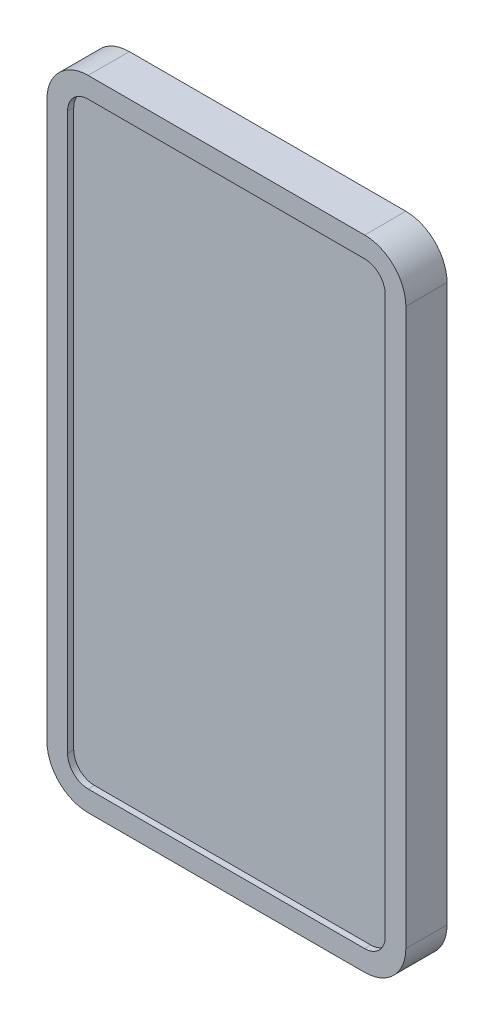
SolidWorks part; units mm, degrees
ref_plane "Plan de face" through (0, 0, 0) normal (0, 0, 1) x (1, 0, 0)
ref_plane "Plan de dessus" through (0, 0, 0) normal (0, 1, 0) x (1, 0, 0)
ref_plane "Plan de droite" through (0, 0, 0) normal (1, 0, 0) x (0, 0, -1)
sketch "Esquisse1" plane through (0, 0, 0) normal (0, 0, 1) x (1, 0, 0)
  line L1 (-67.1082, -155) -> (67.1082, -155)
  line L2 (-87.1082, -135) -> (-87.1082, 135)
  line L3 (-67.1082, 155) -> (67.1082, 155)
  line L4 (87.1082, -135) -> (87.1082, 135)
  line L5 (-87.1082, -155) -> (87.1082, 155) construction
  line L6 (-87.1082, 155) -> (87.1082, -155) construction
  arc A0 (87.1082, -153) -> (85.1082, -155) centre (85.1082, -153) cw
  arc A1 (-85.1082, -155) -> (-87.1082, -153) centre (-85.1082, -153) cw
  arc A2 (-87.1082, 153) -> (-85.1082, 155) centre (-85.1082, 153) cw
  arc A3 (87.1082, 153) -> (85.1082, 155) centre (85.1082, 153) ccw
  arc A4 (-87.1082, -135) -> (-67.1082, -155) centre (-67.1082, -135) ccw
  arc A5 (67.1082, -155) -> (87.1082, -135) centre (67.1082, -135) ccw
  arc A6 (87.1082, 135) -> (67.1082, 155) centre (67.1082, 135) ccw
  arc A7 (-67.1082, 155) -> (-87.1082, 135) centre (-67.1082, 135) ccw
  point P0 (0, 0)
  dimension "D3" = 2
  dimension "D4" = 20
  dimension "D1" = 355.6
  dimension "D2" = 310
extrude "Boss.-Extru.1" add sketch "Esquisse1" along normal blind 20 contours L3 A7 L2 A4 L1 A5 L4 A6
sketch "Esquisse2" plane through (0, 0, 20) normal (0, 0, 1) x (1, 0, 0)
  line L8 (67.1082, 145) -> (-67.1082, 145)
  line L9 (-77.1082, 135) -> (-77.1082, -135)
  line L10 (-67.1082, -145) -> (67.1082, -145)
  line L11 (77.1082, -135) -> (77.1082, 135)
  line L12 (67.1082, 145) -> (-67.1082, 145)
  line L13 (-77.1082, 135) -> (-77.1082, -135)
  line L14 (-67.1082, -145) -> (67.1082, -145)
  line L15 (77.1082, -135) -> (77.1082, 135)
  arc A8 (-67.1082, 145) -> (-77.1082, 135) centre (-67.1082, 135) ccw
  arc A9 (-77.1082, -135) -> (-67.1082, -145) centre (-67.1082, -135) ccw
  arc A10 (67.1082, -145) -> (77.1082, -135) centre (67.1082, -135) ccw
  arc A11 (77.1082, 135) -> (67.1082, 145) centre (67.1082, 135) ccw
  arc A12 (-67.1082, 145) -> (-77.1082, 135) centre (-67.1082, 135) ccw
  arc A13 (-77.1082, -135) -> (-67.1082, -145) centre (-67.1082, -135) ccw
  arc A14 (67.1082, -145) -> (77.1082, -135) centre (67.1082, -135) ccw
  arc A15 (77.1082, 135) -> (67.1082, 145) centre (67.1082, 135) ccw
  dimension "D1" = 10
extrude "Enlèv. mat.-Extru.1" cut sketch "Esquisse2" against normal blind 3
